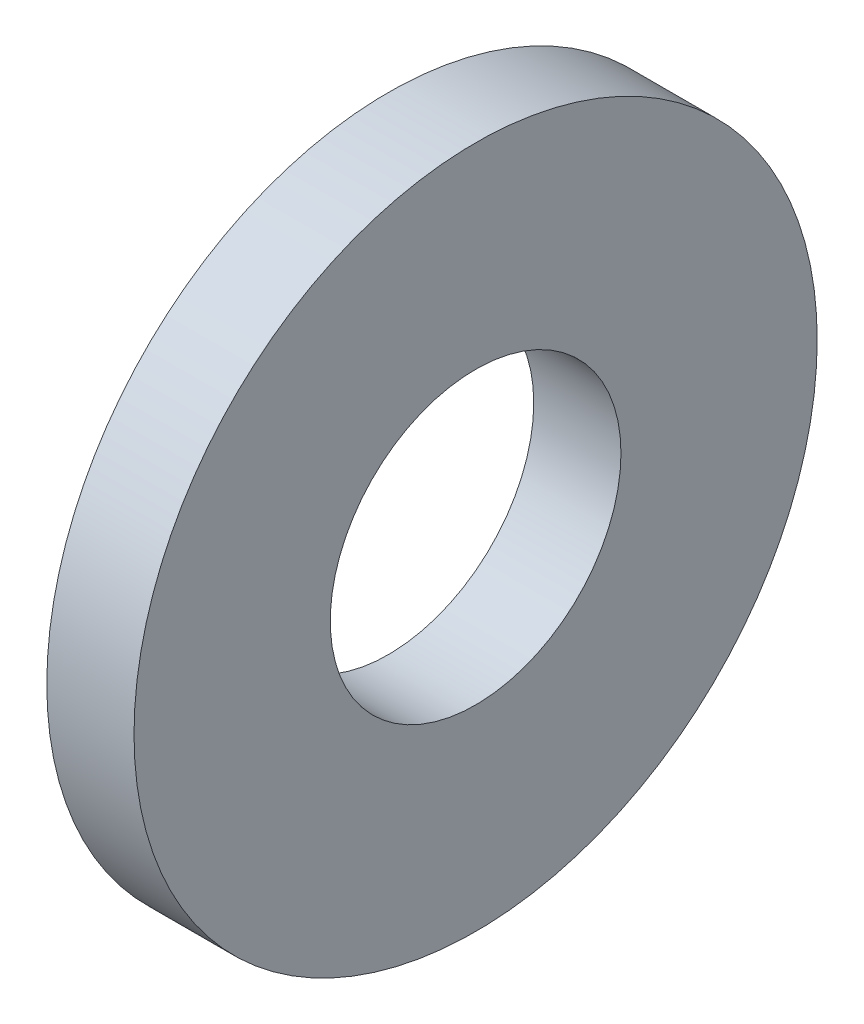
SolidWorks part; units mm, degrees
ref_plane "Front Plane" through (0, 0, 0) normal (0, 0, 1) x (1, 0, 0)
ref_plane "Top Plane" through (0, 0, 0) normal (0, 1, 0) x (1, 0, 0)
ref_plane "Right Plane" through (0, 0, 0) normal (1, 0, 0) x (0, 0, -1)
sketch "Sketch1" plane through (0, 0, 0) normal (1, 0, 0) x (0, 0, -1)
  circle A0 centre (0, 0) radius 11.75
  circle A1 centre (0, 0) radius 5
  dimension "D1" = 23.5
  dimension "D2" = 10
extrude "Boss-Extrude1" add sketch "Sketch1" along normal blind 3
